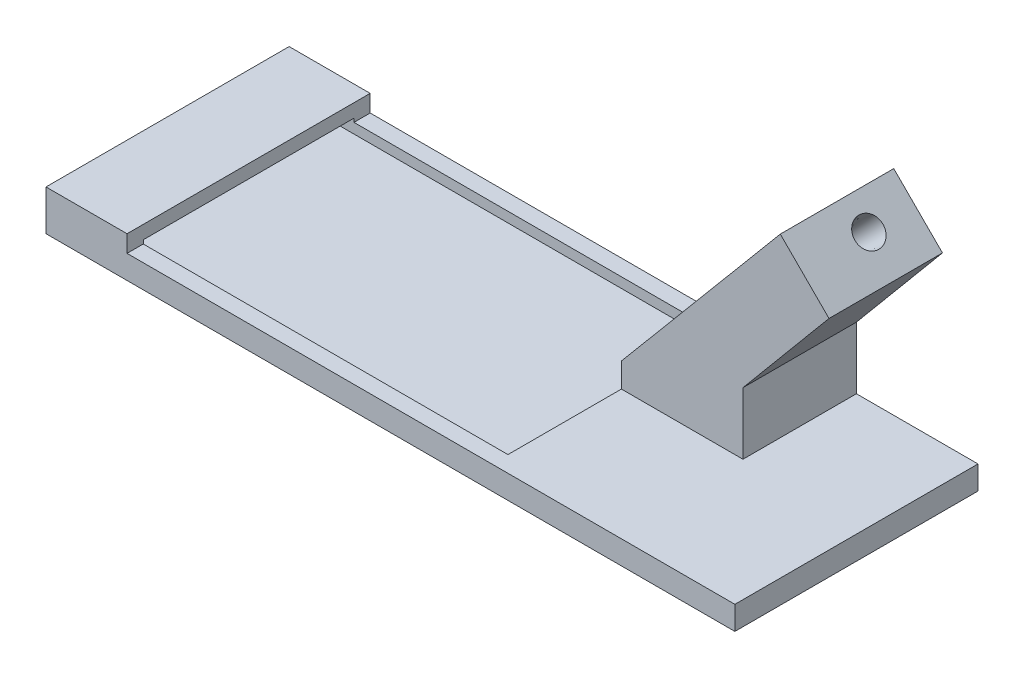
SolidWorks part; units mm, degrees
ref_plane "Front Plane" through (0, 0, 0) normal (0, 0, 1) x (1, 0, 0)
ref_plane "Top Plane" through (0, 0, 0) normal (0, 1, 0) x (1, 0, 0)
ref_plane "Right Plane" through (0, 0, 0) normal (1, 0, 0) x (0, 0, -1)
sketch "Sketch1" plane through (0, 0, 0) normal (0, 1, 0) x (1, 0, 0)
  line L1 (42.5, 15) -> (-42.5, 15)
  line L2 (42.5, 15) -> (42.5, -15)
  line L3 (42.5, -15) -> (-42.5, -15)
  line L4 (-42.5, 15) -> (-42.5, -15)
  line L5 (42.5, 15) -> (-42.5, -15) construction
  line L6 (42.5, -15) -> (-42.5, 15) construction
  point P0 (0, 0)
  dimension "D1" = 85
  dimension "D2" = 30
extrude "Boss-Extrude1" add sketch "Sketch1" along normal blind 5
sketch "Sketch2" plane through (-42.5, 0, 0) normal (-1, 0, 0) x (0, 0, 1)
  line L0 (0, 5) -> (0, 0) construction
  line L1 (-15, 5) -> (15, 5) construction
  line L2 (-15, 2.5) -> (15, 2.5) construction
  line L3 (-15, 5) -> (-15, 0) construction
  line L4 (15, 5) -> (15, 0) construction
  line L6 (13, 3.35) -> (-13, 3.35)
  line L7 (13, 3.35) -> (13, 1.65)
  line L8 (13, 1.65) -> (-13, 1.65)
  line L9 (-13, 3.35) -> (-13, 1.65)
  line L10 (13, 3.35) -> (-13, 1.65) construction
  line L11 (13, 1.65) -> (-13, 3.35) construction
  point P11 (0, 2.5)
  dimension "D1" = 1.7
  dimension "D2" = 26
extrude "Cut-Extrude1" cut sketch "Sketch2" against normal blind 55
sketch "Sketch3" plane through (0, 5, 0) normal (0, 1, 0) x (1, 0, 0)
  line L6 (-42.5, -15) -> (42.5, -15) construction
  line L11 (42.5, 15) -> (-32.5, 15)
  line L12 (42.5, 15) -> (42.5, -15)
  line L13 (42.5, -15) -> (-32.5, -15)
  line L14 (-32.5, 15) -> (-32.5, -15)
  dimension "D1" = 75
extrude "Cut-Extrude2" cut sketch "Sketch3" against normal blind 2.1
sketch "Sketch10" plane through (0, 0, -15) normal (0, 0, -1) x (-1, 0, 0)
  line L1 (-27.5, 2.9) -> (-12.5, 2.9)
  line L2 (-42.5, 2.9) -> (32.5, 2.9) construction
  line L3 (-12.5, 2.9) -> (-12.5, 5.9)
  line L4 (-12.5, 5.9) -> (-32.105, 29.2644)
  line L6 (-38.1154, 23.2539) -> (-27.5, 10.5527)
  line L7 (-27.5, 2.9) -> (-27.5, 10.5527)
  line L8 (-32.105, 29.2644) -> (-38.1154, 23.2539)
  dimension "D1" = 15
  dimension "D2" = 3
  dimension "D3" = 50
  dimension "D4" = 30.5
  dimension "D5" = 8.5
  dimension "D6" = 7.6527
  dimension "D7" = 85
extrude "Boss-Extrude5" add sketch "Sketch10" against normal blind 14
sketch "Sketch13" plane through (12.5, 0, 0) normal (-1, 0, 0) x (0, 0, 1)
  line L0 (-15, 4.4) -> (-1, 4.4) construction
  line L1 (-15, 2.9) -> (-15, 5.9) construction
  line L2 (-1, 2.9) -> (-1, 5.9) construction
ref_plane "Plane2" through (4.05, -4.05, 0) normal (-0.7071, 0.7071, 0) x (0, 0, 1)
sketch "Sketch14" plane through (4.05, -4.05, 0) normal (-0.7071, 0.7071, 0) x (0, 0, 1)
  line L1 (-13, 10.0056) -> (13, 10.0056) construction
  line L4 (-9.8, 10.0056) -> (-9.2, 10.0056)
  line L11 (-9.8, 10.0056) -> (-11.05, 43.9054)
  line L12 (-11.05, 43.9054) -> (-9.3, 43.9054)
  line L15 (-9.2, 10.0056) -> (-9.3, 43.9054)
  dimension "D1" = 0.6
  dimension "D2" = 33.9
  dimension "D3" = 3.2
  dimension "D4" = 1.75
  dimension "D5" = 1.25
revolve "Cut-Revolve5" cut sketch "Sketch14" angle 360 about L15
